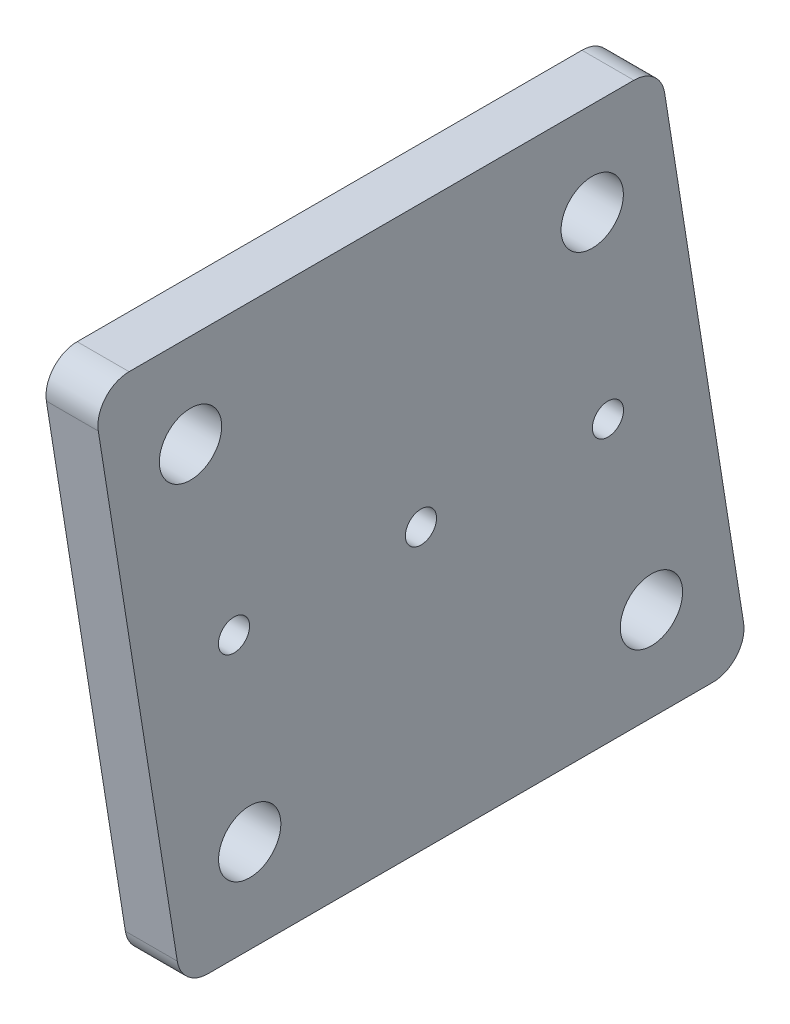
SolidWorks part; units mm, degrees
ref_plane "Front Plane" through (0, 0, 0) normal (0, 0, 1) x (1, 0, 0)
ref_plane "Top Plane" through (0, 0, 0) normal (0, 1, 0) x (1, 0, 0)
ref_plane "Right Plane" through (0, 0, 0) normal (1, 0, 0) x (0, 0, -1)
sketch "Sketch1" plane through (0, 0, 0) normal (1, 0, 0) x (0, 0, -1)
  line L0 (-0.5463, 45) -> (8.0065, -9) construction
  line L2 (24.9678, 45) -> (33.5206, -9) construction
  line L4 (0, 0) -> (38.6762, 0) construction
  line L5 (0, 0) -> (-5.7018, 36) construction
  line L6 (38.6762, 0) -> (32.9743, 36) construction
  line L7 (-5.7018, 36) -> (32.9743, 36) construction
  line L8 (-2.8509, 18) -> (35.8252, 18) construction
  line L9 (-4.4348, 28) -> (34.2414, 28) construction
  line L10 (-1.2671, 8) -> (37.4091, 8) construction
  line L11 (-6.573, -9) -> (48.1001, -9)
  line L12 (48.1001, -9) -> (39.5473, 45)
  line L13 (39.5473, 45) -> (-15.1258, 45)
  line L14 (-15.1258, 45) -> (-6.573, -9)
  line L15 (-2.8509, 18) -> (-10.8494, 18) construction
  line L16 (16.4872, 18) -> (20.7635, -9) construction
  circle A0 centre (0, 0) radius 6.5 construction
  circle A1 centre (0, 0) radius 7.5 construction
  circle A2 centre (0, 0) radius 3
  circle A3 centre (38.6762, 0) radius 3
  circle A4 centre (38.6762, 0) radius 6.5 construction
  circle A5 centre (38.6762, 0) radius 7.5 construction
  circle A6 centre (-5.7018, 36) radius 3
  circle A7 centre (-5.7018, 36) radius 6.5 construction
  circle A8 centre (-5.7018, 36) radius 7.5 construction
  circle A9 centre (32.9743, 36) radius 3
  circle A10 centre (32.9743, 36) radius 6.5 construction
  circle A11 centre (32.9743, 36) radius 7.5 construction
  circle A12 centre (16.4872, 18) radius 1.5
  circle A13 centre (-1.5128, 18) radius 1.5
  circle A14 centre (34.4872, 18) radius 1.5
  dimension "D1" = 15
  dimension "D2" = 13
  dimension "D3" = 6
  dimension "D9" = 18
  dimension "D10" = 18
  dimension "D11" = 3
  dimension "D4" = 81
  dimension "D5" = 25.2
  dimension "D6" = 36
  dimension "D7" = 10
  dimension "D8" = 10
  dimension "D12" = 54
  dimension "D13" = 54
  dimension "D15" = 54
extrude "Boss-Extrude1" add sketch "Sketch1" along normal blind 5
fillet "Fillet1" radius 3 4 edges at (2.5, 45, -39.5473) (2.5, -9, -48.1001) (2.5, -9, 6.573) (2.5, 45, 15.1258)
